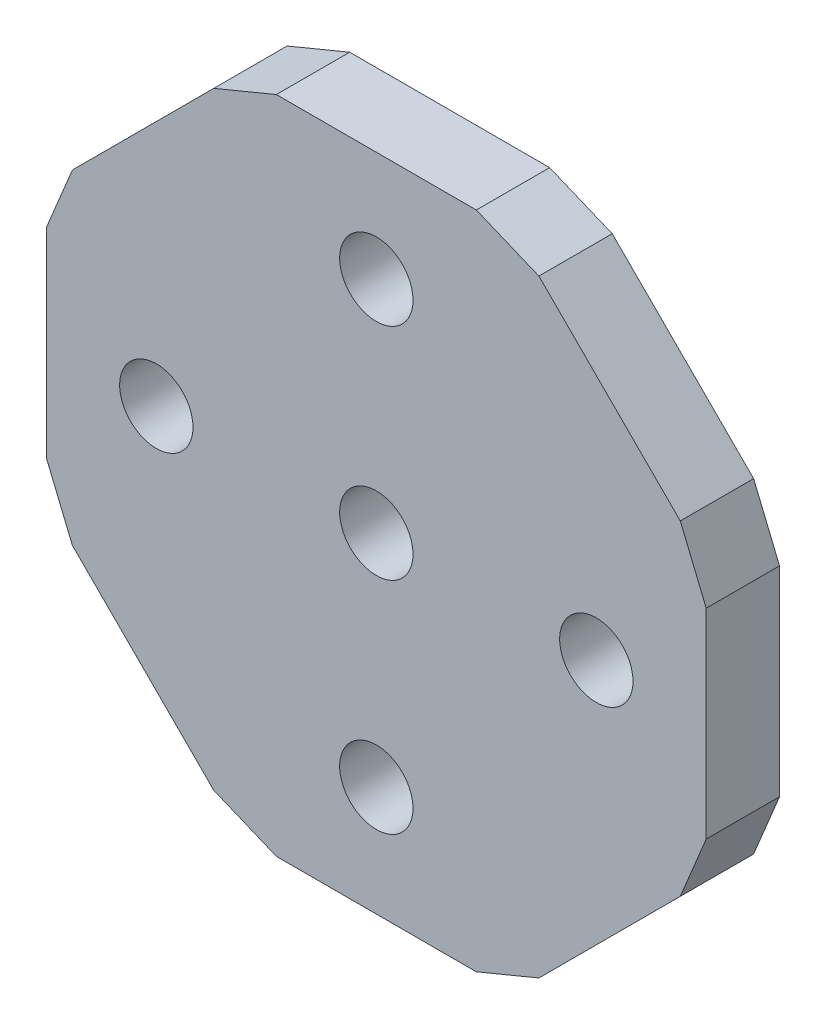
SolidWorks part; units mm, degrees
ref_plane "Alzado" through (0, 0, 0) normal (0, 0, 1) x (1, 0, 0)
ref_plane "Planta" through (0, 0, 0) normal (0, 1, 0) x (1, 0, 0)
ref_plane "Vista lateral" through (0, 0, 0) normal (1, 0, 0) x (0, 0, -1)
sketch "Model" plane through (0, 0, 0) normal (0, 0, 1) x (1, 0, 0)
  line L0 (219.8376, 228.457) -> (211.658, 228.457)
  line L1 (211.658, 255.447) -> (219.8376, 255.447)
  line L2 (209.0973, 229.5177) -> (203.3135, 235.3015)
  line L3 (202.2528, 237.8622) -> (202.2528, 246.0418)
  line L4 (203.3135, 248.6025) -> (209.0973, 254.3864)
  line L5 (228.1821, 235.3015) -> (222.3983, 229.5177)
  line L6 (222.3983, 254.3864) -> (228.1821, 248.6025)
  line L7 (229.2428, 246.0418) -> (229.2428, 237.8622)
  line L8 (202.2528, 246.0418) -> (203.3135, 248.6025)
  line L9 (202.2528, 237.8622) -> (203.3135, 235.3015)
  line L10 (209.0973, 229.5177) -> (211.658, 228.457)
  line L11 (222.3983, 229.5177) -> (219.8376, 228.457)
  line L12 (228.1821, 235.3015) -> (229.2428, 237.8622)
  line L13 (229.2428, 246.0418) -> (228.1821, 248.6025)
  line L14 (222.3983, 254.3864) -> (219.8376, 255.447)
  line L15 (211.658, 255.447) -> (209.0973, 254.3864)
  circle A0 centre (215.7478, 241.952) radius 1.5
  circle A1 centre (215.7478, 232.952) radius 1.5
  circle A2 centre (215.7478, 250.952) radius 1.5
  circle A3 centre (224.7478, 241.952) radius 1.5
  circle A4 centre (206.7478, 241.952) radius 1.5
extrude "Saliente-Extruir1" add sketch "Model" along normal blind 3
